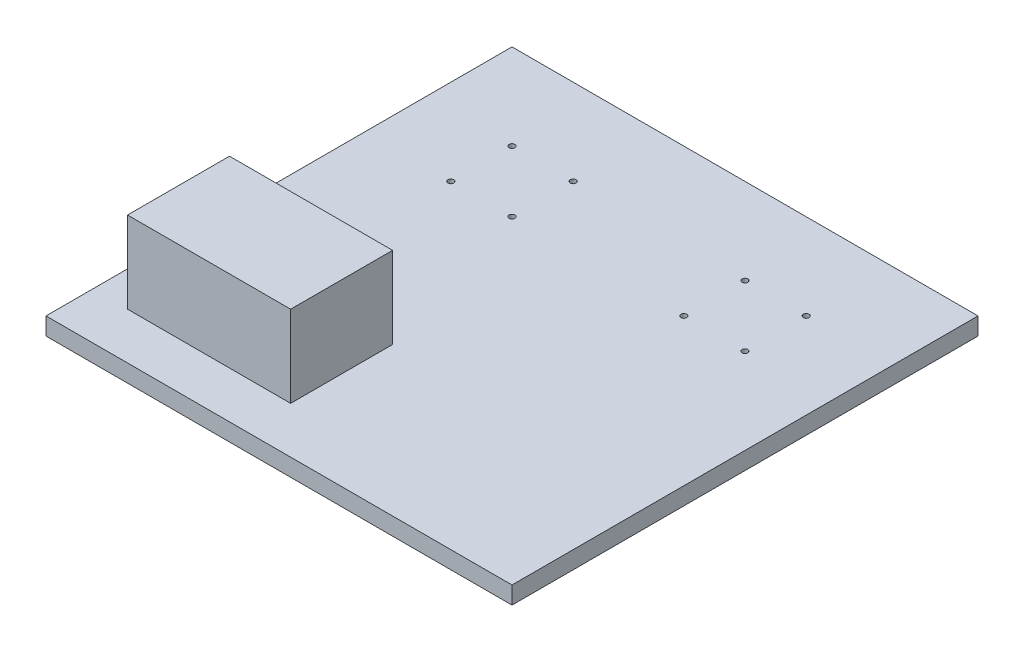
SolidWorks part; units mm, degrees
ref_plane "正面" through (0, 0, 0) normal (0, 0, 1) x (1, 0, 0)
ref_plane "平面" through (0, 0, 0) normal (0, 1, 0) x (1, 0, 0)
ref_plane "右側面" through (0, 0, 0) normal (1, 0, 0) x (0, 0, -1)
sketch "ｽｹｯﾁ1" plane through (0, 0, 0) normal (0, 1, 0) x (1, 0, 0)
  line L1 (-40, 40) -> (40, 40)
  line L2 (-40, 40) -> (-40, -40)
  line L3 (-40, -40) -> (40, -40)
  line L4 (40, 40) -> (40, -40)
extrude "ﾎﾞｽ - 押し出し1" add sketch "ｽｹｯﾁ1" along normal blind 6
sketch "ｽｹｯﾁ2" plane through (0, 6, 0) normal (0, 1, 0) x (1, 0, 0)
  circle A0 centre (-10.5, 10.5) radius 1
  circle A1 centre (10.5, 10.5) radius 1
  circle A2 centre (10.5, -10.5) radius 1
  circle A3 centre (-10.5, -10.5) radius 1
  dimension "D1" = 2
  dimension "D3" = 2
  dimension "D2" = 2
extrude "ｶｯﾄ - 押し出し1" cut sketch "ｽｹｯﾁ2" against normal through all
mirror "ﾐﾗｰ9" about plane through (40, 6, -40) normal (-1, 0, 0) of "ｶｯﾄ - 押し出し1", "ﾎﾞｽ - 押し出し1"
mirror "ﾐﾗｰ10" about plane through (-40, 6, 40) normal (0, 0, -1) of "ﾎﾞｽ - 押し出し1"
sketch "ｽｹｯﾁ3" plane through (40, 0, 0) normal (1, 0, 0) x (0, 0, -1)
  line L1 (-120, 6) -> (-40, 6)
  line L2 (-120, 6) -> (-120, 0)
  line L3 (-120, 0) -> (-40, 0)
  line L4 (-40, 6) -> (-40, 0)
extrude "ﾎﾞｽ - 押し出し2" add sketch "ｽｹｯﾁ3" along normal blind 80
sketch "ｽｹｯﾁ4" plane through (0, 6, 0) normal (0, 1, 0) x (1, 0, 0)
  line L1 (-28, -69) -> (28, -69)
  line L2 (-28, -69) -> (-28, -104)
  line L3 (-28, -104) -> (28, -104)
  line L4 (28, -69) -> (28, -104)
  point P4 (0, 0)
  point P5 (0, 0)
  point P6 (0, 0)
  point P7 (0, 0)
  point P8 (0, 0)
  point P9 (0, 0)
  dimension "D1" = 56
  dimension "D2" = 35
extrude "ﾎﾞｽ - 押し出し3" add sketch "ｽｹｯﾁ4" along normal blind 28
sketch "ｽｹｯﾁ5" plane through (0, 0, 69) normal (0, 0, -1) x (-1, 0, 0)
  line L0 (-28, 6) -> (28, 6) construction
  line L1 (-24, 30) -> (24, 30)
  line L2 (-24, 30) -> (-24, 6)
  line L3 (-24, 6) -> (24, 6)
  line L4 (24, 30) -> (24, 6)
  line L5 (-28, 34) -> (28, 34) construction
  dimension "D1" = 4
  dimension "D2" = 4
  dimension "D3" = 4
extrude "ｶｯﾄ - 押し出し2" cut sketch "ｽｹｯﾁ5" against normal blind 31
